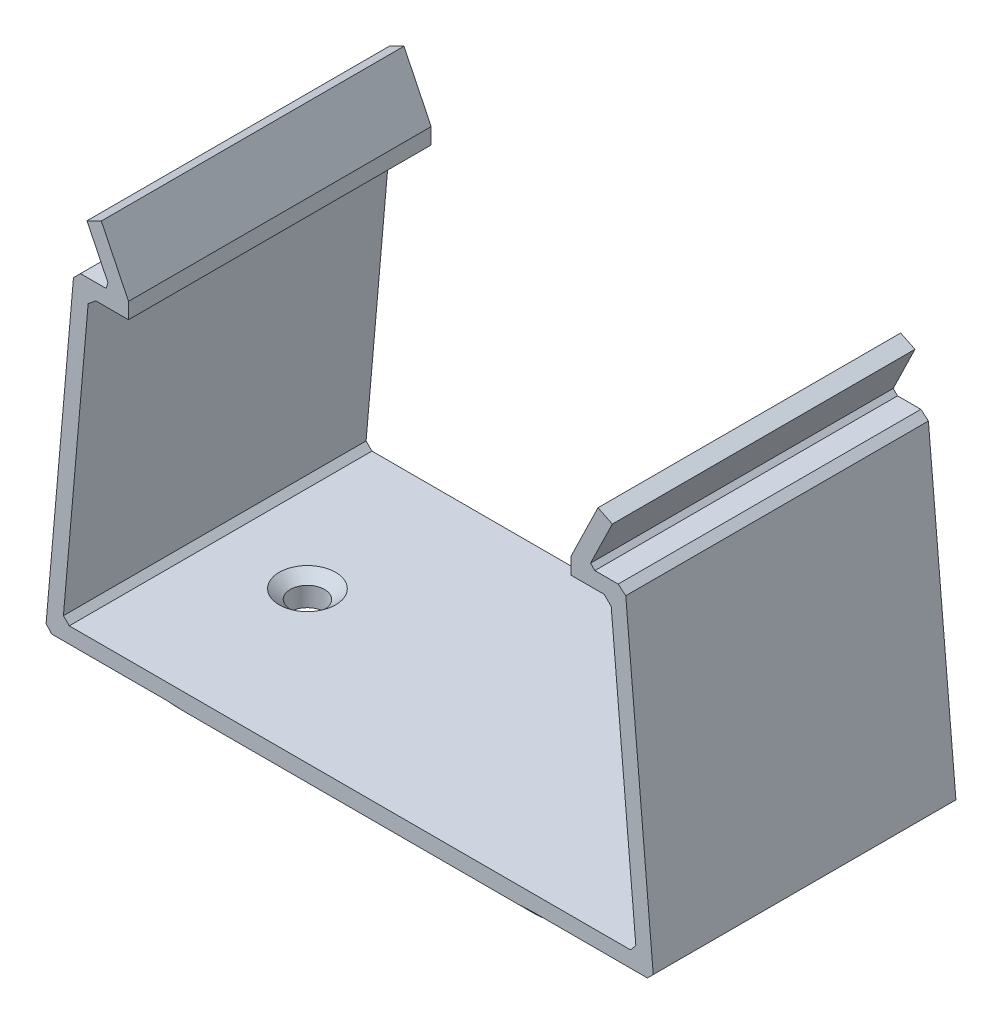
SolidWorks part; units mm, degrees
ref_plane "Front Plane" through (0, 0, 0) normal (0, 0, 1) x (1, 0, 0)
ref_plane "Top Plane" through (0, 0, 0) normal (0, 1, 0) x (1, 0, 0)
ref_plane "Right Plane" through (0, 0, 0) normal (1, 0, 0) x (0, 0, -1)
sketch "Sketch1" plane through (0, 0, 0) normal (0, 0, 1) x (1, 0, 0)
  line L0 (0, 0) -> (0, 24) construction
  line L1 (-34.5956, 39) -> (-29.9866, 39)
  line L2 (-32.7629, 37) -> (-36, 0)
  line L3 (-36, 0) -> (0, 0)
  line L4 (-34.5956, 39) -> (-38.1826, -2)
  line L5 (-38.1826, -2) -> (0, -2)
  line L6 (-32.7629, 37) -> (-27.7629, 37)
  line L7 (-27.7629, 39) -> (-27.7629, 37)
  line L8 (38.1826, -2) -> (0, -2)
  line L9 (36, 0) -> (0, 0)
  line L10 (27.7629, 39) -> (27.7629, 37)
  line L11 (32.7629, 37) -> (27.7629, 37)
  line L12 (34.5956, 39) -> (38.1826, -2)
  line L13 (32.7629, 37) -> (36, 0)
  line L14 (34.5956, 39) -> (29.9866, 39)
  line L15 (-27.7629, 39) -> (-31.1793, 46.0303)
  line L16 (-29.9866, 39) -> (-32.9781, 45.1562)
  line L17 (-31.1793, 46.0303) -> (-32.9781, 45.1562)
  line L18 (-29.5618, 38.1259) -> (-32.9781, 45.1562) construction
  line L19 (-34.5956, 39) -> (-27.7629, 39) construction
  line L20 (31.1793, 46.0303) -> (32.9781, 45.1562)
  line L21 (29.9866, 39) -> (32.9781, 45.1562)
  line L22 (27.7629, 39) -> (31.1793, 46.0303)
  dimension "D1" = 85
  dimension "D2" = 37
  dimension "D3" = 36
  dimension "D4" = 2
  dimension "D5" = 5
  dimension "D6" = 2
extrude "Boss-Extrude1" add sketch "Sketch1" along normal blind 38
sketch "Sketch5" plane through (0, -2, 0) normal (0, -1, 0) x (1, 0, 0)
  line L0 (-31.5, 0) -> (-31.5, 38)
  line L1 (-38.1826, 38) -> (38.1826, 38) construction
  line L3 (-31.5, 38) -> (31.5, 38)
  line L4 (-31.5, 0) -> (31.5, 0)
  line L5 (0, 0) -> (0, 50) construction
  line L6 (24.3, 15) -> (-24.3, 15) construction
  line L7 (31.5, 0) -> (31.5, 38)
  dimension "D1" = 48.6
  dimension "D2" = 63
extrude "Boss-Extrude2" add sketch "Sketch5" along normal blind 1.6
sketch "Sketch9" plane through (0, 0, 0) normal (0, 1, 0) x (1, 0, 0)
  line L1 (-5, -34) -> (-5, -4)
  line L2 (-5, -34) -> (5, -34)
  line L3 (5, -34) -> (5, -4)
  line L4 (-5, -4) -> (5, -4)
  line L5 (-5, -34) -> (5, -4) construction
  line L6 (5, -34) -> (-5, -4) construction
  point P0 (0, -19)
  dimension "D1" = 10
  dimension "D3" = 30
extrude "Cut-Extrude4" [suppressed] cut sketch "Sketch9" against normal blind 1.5
chamfer "Chamfer4" [suppressed] distance 1.5 angle 45
chamfer "Chamfer6" distance 0.8 angle 45 4 edges at (-38.1826, -2, 19) (38.1826, -2, 19) (36, 0, 19) (-36, 0, 19)
chamfer "Chamfer7" distance 0.8 angle 45 6 edges at (-32.7629, 37, 19) (32.7629, 37, 19) (34.5956, 39, 19) (-34.5956, 39, 19) (29.9866, 39, 19) (-29.9866, 39, 19)
sketch "Sketch12" plane through (0, 0, 0) normal (0, 1, 0) x (1, 0, 0)
  line L0 (24.3, -19) -> (-24.3, -19) construction
  dimension "D1" = 48.6
hole_wizard "CSK for #6 Flat Head Machine Screw (100)1" positions "Sketch13" profile "Sketch14" countersink size "#6" standard "ANSI Inch"
sketch "Sketch13" plane through (0, 0, 0) normal (0, 1, 0) x (1, 0, 0)
  point P0 (24.3, -19)
  point P3 (-24.3, -19)
sketch "Sketch14" plane through (24.3, 0, 19) normal (1, 0, 0) x (0, 0, 1)
  line L0 (0, 0) -> (0, 3.6)
  line L1 (0, 3.6) -> (2.1526, 3.6)
  line L2 (2.1526, 3.6) -> (2.1526, 1.1669)
  line L3 (2.1526, 1.1669) -> (3.5433, 0)
  line L5 (3.5433, 0) -> (0, 0)
  line L6 (-2.1526, 1.1669) -> (-3.5433, 0) construction
  line L11 (0, -6.35) -> (0, 107.95) construction
  dimension "Thru Hole Dia." = 4.3053
  dimension "Thru Hole Depth" = 3.6
  dimension "Near C'Sink Dia." = 7.0866
  dimension "Near C'Sink Angle" = 100
fillet "Fillet1" radius 10 4 edges at (-31.5, -2.8, 38) (-31.5, -2.8, 0) (31.5, -2.8, 0) (31.5, -2.8, 38)
chamfer "Chamfer10" distance 1.5 angle 45 8 edges at (31.5, -3.6, 19) (28.5711, -3.6, 35.0711) (28.5711, -3.6, 2.9289) (0, -3.6, 38) (0, -3.6, 0) (-28.5711, -3.6, 35.0711) (-28.5711, -3.6, 2.9289) (-31.5, -3.6, 19)
